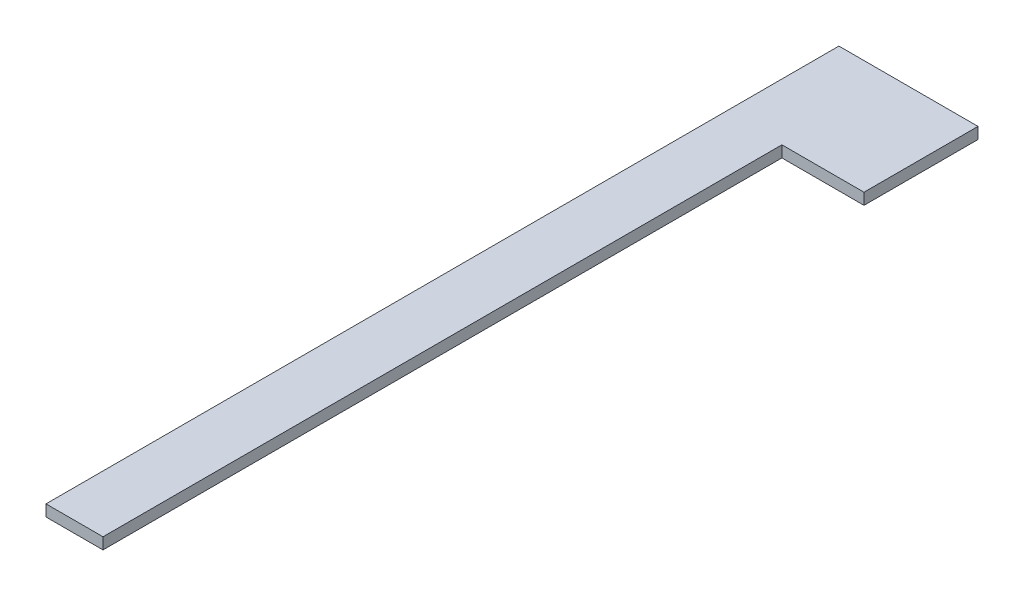
SolidWorks part; units mm, degrees
material "7075-T6 (SN)"
ref_plane "Front Plane" through (0, 0, 0) normal (0, 0, 1) x (1, 0, 0)
ref_plane "Top Plane" through (0, 0, 0) normal (0, 1, 0) x (1, 0, 0)
ref_plane "Right Plane" through (0, 0, 0) normal (1, 0, 0) x (0, 0, -1)
sketch "Sketch2" plane through (0, 0, 0) normal (0, 1, 0) x (1, 0, 0)
  line L1 (-10.0446, -31.9274) -> (-5.0446, -31.9274)
  line L2 (-10.0446, -31.9274) -> (-10.0446, -91.4774)
  line L3 (-10.0446, -91.4774) -> (-5.0446, -91.4774)
  line L4 (-5.0446, -31.9274) -> (-5.0446, -91.4774)
  line L5 (-10.0446, -31.9274) -> (2.1554, -31.9274)
  line L6 (-10.0446, -31.9274) -> (-10.0446, -21.9274)
  line L7 (-10.0446, -21.9274) -> (2.1554, -21.9274)
  line L8 (2.1554, -31.9274) -> (2.1554, -21.9274)
  dimension "D1" = 59.55
  dimension "D2" = 10
  dimension "D3" = 5
  dimension "D4" = 12.2
extrude "Boss-Extrude2" add sketch "Sketch2" along normal blind 1 contours L4 L1 L2 L3 | L5 L8 L7 L6 L1
